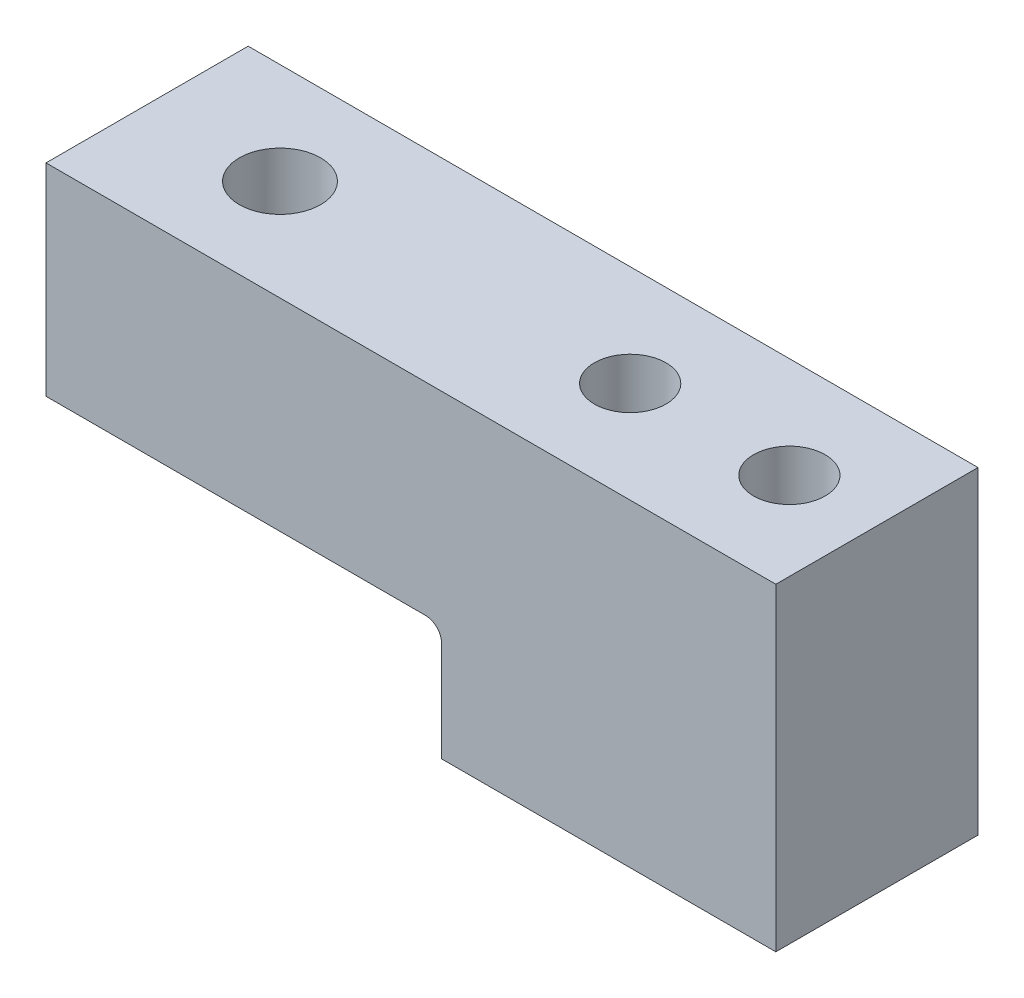
SolidWorks part; units mm, degrees
ref_plane "Front Plane" through (0, 0, 0) normal (0, 0, 1) x (1, 0, 0)
ref_plane "Top Plane" through (0, 0, 0) normal (0, 1, 0) x (1, 0, 0)
ref_plane "Right Plane" through (0, 0, 0) normal (1, 0, 0) x (0, 0, -1)
sketch "Sketch1" plane through (0, 0, 0) normal (0, 0, 1) x (1, 0, 0)
  line L0 (0, 0) -> (21, 0)
  line L1 (21, 0) -> (21, 20)
  line L2 (21, 20) -> (-24.85, 20)
  line L3 (-24.85, 20) -> (-24.85, 7.3)
  line L4 (-24.85, 7.3) -> (-1, 7.3)
  line L5 (0, 6.3) -> (0, 0)
  arc A1 (0, 6.3) -> (-1, 7.3) centre (-1, 6.3) ccw
  point P6 (0, 7.3)
  point P9 (0, 0)
  dimension "D1" = 1
  dimension "D2" = 7.3
  dimension "D3" = 20
  dimension "D4" = 45.85
  dimension "D5" = 24.85
extrude "Boss-Extrude1" add sketch "Sketch1" along normal blind 12.7
hole_wizard "M4 Clearance Hole1" positions "Sketch2" profile "Sketch3" hole size "M4" standard "ANSI Metric" end condition through all
sketch "Sketch2" plane through (0, 20, 0) normal (0, 1, 0) x (1, 0, 0)
  line L0 (21, -12.7) -> (21, 0) construction
  line L1 (21, -12.7) -> (-24.85, -12.7) construction
  point P0 (5.5, -6.35)
  point P2 (15.5, -6.35)
  dimension "D1" = 5.5
  dimension "D2" = 6.35
  dimension "D3" = 10
sketch "Sketch3" plane through (5.5, 20, 6.35) normal (1, 0, 0) x (0, 0, 1)
  line L0 (0, 0) -> (0, 20)
  line L1 (0, 20) -> (2.25, 20)
  line L2 (2.25, 20) -> (2.25, 0)
  line L5 (2.25, 0) -> (0, 0)
  line L11 (0, -6.35) -> (0, 107.95) construction
  dimension "Thru Hole Dia." = 4.5
  dimension "Thru Hole Depth" = 20
hole_wizard "Tap Drill for 1/4-20 Tap1" positions "Sketch4" profile "Sketch5" hole size "1/4-20" standard "ANSI Inch" end condition through all
sketch "Sketch4" plane through (0, 20, 0) normal (0, 1, 0) x (1, 0, 0)
  line L0 (-24.85, -12.7) -> (-24.85, 0) construction
  line L1 (21, 0) -> (-24.85, 0) construction
  point P0 (-16.5, -6.35)
  dimension "D1" = 8.35
  dimension "D2" = 6.35
sketch "Sketch5" plane through (-16.5, 20, 6.35) normal (1, 0, 0) x (0, 0, 1)
  line L0 (0, 0) -> (0, 20)
  line L1 (0, 20) -> (2.5527, 20)
  line L2 (2.5527, 20) -> (2.5527, 0)
  line L5 (2.5527, 0) -> (0, 0)
  line L11 (0, -6.35) -> (0, 107.95) construction
  dimension "Thru Hole Dia." = 5.1054
  dimension "Thru Hole Depth" = 20
